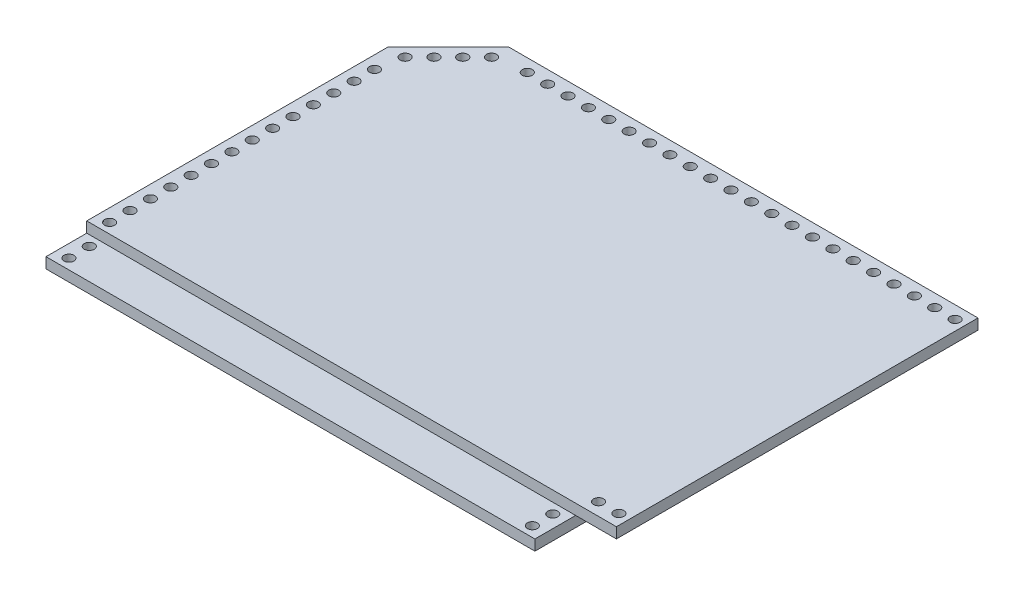
SolidWorks part; units mm, degrees
ref_plane "Front Plane" through (0, 0, 0) normal (0, 0, 1) x (1, 0, 0)
ref_plane "Top Plane" through (0, 0, 0) normal (0, 1, 0) x (1, 0, 0)
ref_plane "Right Plane" through (0, 0, 0) normal (1, 0, 0) x (0, 0, -1)
sketch "Sketch2" plane through (0, 0, 0) normal (0, 1, 0) x (1, 0, 0)
  line L0 (-73.1672, 26.9845) -> (-55.2067, 44.945)
  line L1 (-73.1672, 44.945) -> (85.3288, 44.945)
  line L2 (-73.1672, 44.945) -> (-73.1672, -75.451)
  line L3 (-73.1672, -75.451) -> (85.3288, -75.451)
  line L4 (85.3288, 44.945) -> (85.3288, -75.451)
  dimension "D1" = 158.496
  dimension "D2" = 120.396
  dimension "D3" = 25.4
  dimension "D4" = 45
extrude "Boss-Extrude1" add sketch "Sketch2" along normal blind 6.35 contours L4 L1 L0 L2 L3
sketch "Sketch3" plane through (0, 6.35, 0) normal (0, 1, 0) x (1, 0, 0)
  line L0 (-55.2067, 44.945) -> (85.3288, 44.945) construction
  line L1 (85.3288, 44.945) -> (85.3288, -75.451) construction
  circle A0 centre (82.2808, 41.135) radius 1.5
  dimension "D3" = 3
  dimension "D1" = 3.81
  dimension "D2" = 3.048
extrude "Cut-Extrude1" cut sketch "Sketch3" against normal blind 6.35 contours A0
pattern_linear "LPattern2" count 22 spacing 6.096 along (-1, 0, 0) of "Cut-Extrude1"
sketch "Sketch4" plane through (0, 6.35, 0) normal (0, 1, 0) x (1, 0, 0)
  line L0 (-73.1672, 26.9845) -> (-73.1672, -75.451) construction
  line L1 (-73.1672, -75.451) -> (85.3288, -75.451) construction
  circle A0 centre (-69.3572, -72.403) radius 1.5
  dimension "D1" = 3
  dimension "D2" = 3.81
  dimension "D3" = 3.048
extrude "Cut-Extrude2" cut sketch "Sketch4" against normal blind 6.35
pattern_linear "LPattern3" count 16 spacing 6.096 along (0, 0, -1) of "Cut-Extrude2"
sketch "Sketch6" plane through (85.3288, 0, 0) normal (1, 0, 0) x (0, 0, -1)
  line L0 (44.945, 6.35) -> (-75.451, 6.35) construction
  line L1 (-75.451, 3.175) -> (44.945, 3.175)
  line L2 (-75.451, 3.175) -> (-75.451, 0)
  line L3 (-75.451, 0) -> (44.945, 0)
  line L4 (44.945, 3.175) -> (44.945, 0)
  line L5 (-75.451, 6.35) -> (-75.451, 0) construction
  line L6 (44.945, 6.35) -> (44.945, 0) construction
  dimension "D1" = 3.175
  dimension "D2" = 3.175
  dimension "D3" = 0
  dimension "D4" = 0
extrude "Cut-Extrude3" cut sketch "Sketch6" against normal blind 12.192
sketch "Sketch10" plane through (0, 6.35, 0) normal (0, 1, 0) x (1, 0, 0)
  line L1 (85.3288, -75.451) -> (73.1368, -75.451)
  line L2 (85.3288, -75.451) -> (85.3288, -63.259)
  line L3 (85.3288, -63.259) -> (73.1368, -63.259)
  line L4 (73.1368, -75.451) -> (73.1368, -63.259)
  dimension "D1" = 12.192
  dimension "D2" = 12.192
extrude "Cut-Extrude9" cut sketch "Sketch10" against normal blind 12.192
sketch "Sketch9" plane through (0, 0, 75.451) normal (0, 0, 1) x (1, 0, 0)
  line L0 (85.3288, 6.35) -> (85.3288, 3.175) construction
  line L1 (-73.1672, 6.35) -> (73.1368, 6.35)
  line L2 (-73.1672, 6.35) -> (-73.1672, 3.175)
  line L3 (-73.1672, 3.175) -> (73.1368, 3.175)
  line L4 (73.1368, 6.35) -> (73.1368, 3.175)
  dimension "D1" = 12.192
extrude "Cut-Extrude8" cut sketch "Sketch9" against normal blind 12.192
sketch "Sketch11" plane through (0, 6.35, 0) normal (0, 1, 0) x (1, 0, 0)
  line L0 (85.3288, -63.259) -> (-73.1672, -63.259) construction
  line L1 (85.3288, 44.945) -> (85.3288, -63.259) construction
  line L4 (73.1368, -63.259) -> (73.1368, -75.451) construction
  line L5 (-73.1672, -75.451) -> (73.1368, -75.451) construction
  circle A0 centre (82.2808, -59.449) radius 1.5
  circle A1 centre (76.1848, -59.449) radius 1.5
  circle A2 centre (69.3268, -66.307) radius 1.5
  circle A3 centre (69.3268, -72.403) radius 1.5
  dimension "D1" = 3.81
  dimension "D4" = 3
  dimension "D5" = 3
  dimension "D7" = 3.81
  dimension "D8" = 3.048
  dimension "D9" = 3.81
  dimension "D11" = 3
  dimension "D12" = 3
  dimension "D2" = 3.048
  dimension "D3" = 3.81
  dimension "D6" = 6.096
  dimension "D10" = 6.096
extrude "Cut-Extrude10" cut sketch "Sketch11" against normal blind 6.35
sketch "Sketch13" plane through (0, 6.35, 0) normal (0, 1, 0) x (1, 0, 0)
  line L0 (-55.2067, 44.945) -> (-55.2067, 26.9845)
  line L1 (-55.2067, 26.9845) -> (-73.1672, 26.9845)
  line L2 (-73.1672, 26.9845) -> (-55.2067, 44.945)
  line L3 (-55.2067, 26.9845) -> (-64.1869, 35.9647)
  circle A0 centre (-59.3376, 35.4259) radius 1.5
  circle A1 centre (-55.0271, 39.7365) radius 1.5
  circle A2 centre (-63.6481, 31.1154) radius 1.5
  circle A3 centre (-67.9587, 26.8049) radius 1.5
  point P14 (0, 0)
  point P16 (0, 0)
  dimension "D9" = 3
  dimension "D10" = 3
  dimension "D11" = 3
  dimension "D12" = 3
  dimension "D1" = 3.048
  dimension "D2" = 3.048
  dimension "D3" = 6.096
  dimension "D4" = 6.096
  dimension "D5" = 3.81
  dimension "D6" = 3.81
  dimension "D7" = 3.81
  dimension "D8" = 3.81
extrude "Cut-Extrude12" cut sketch "Sketch13" against normal blind 6.35 contours A0 | A1 | A2 | A3
